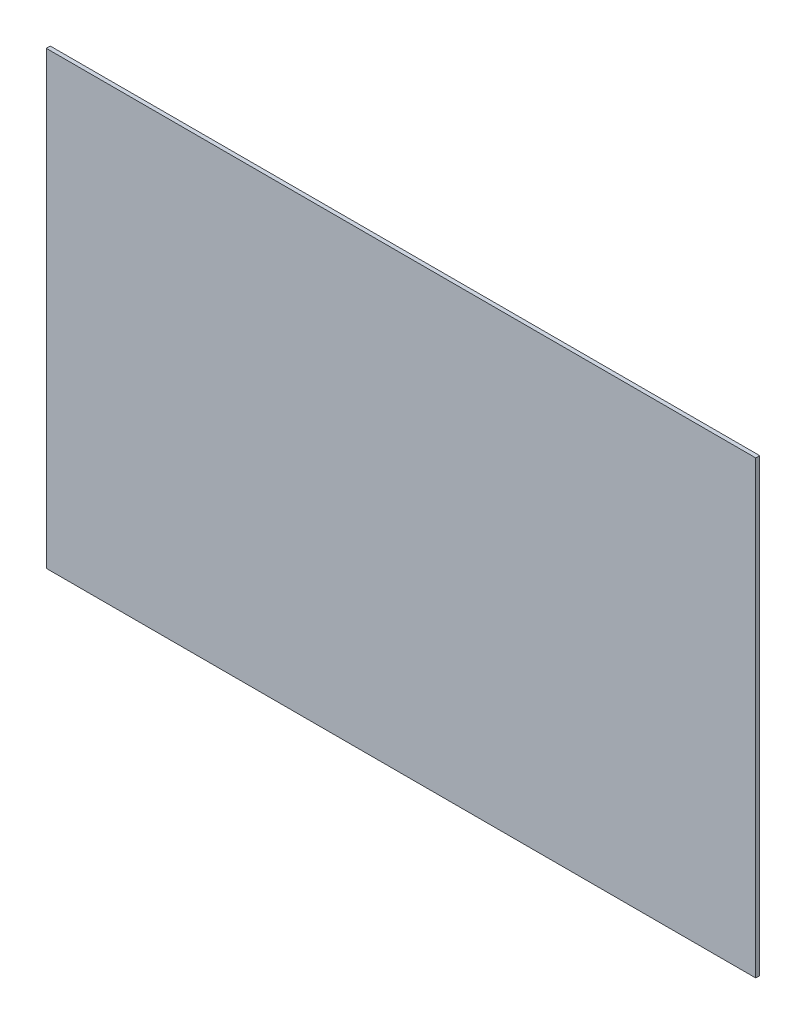
SolidWorks part; units mm, degrees
ref_plane "Plano frontal" through (0, 0, 0) normal (0, 0, 1) x (1, 0, 0)
ref_plane "Plano superior" through (0, 0, 0) normal (0, 1, 0) x (1, 0, 0)
ref_plane "Plano direito" through (0, 0, 0) normal (1, 0, 0) x (0, 0, -1)
sketch "Esboço1" plane through (0, 0, 0) normal (0, 0, 1) x (1, 0, 0)
  line L1 (-146.3409, 96.5423) -> (31.6591, 96.5423)
  line L2 (-146.3409, 96.5423) -> (-146.3409, -16.4577)
  line L3 (-146.3409, -16.4577) -> (31.6591, -16.4577)
  line L4 (31.6591, 96.5423) -> (31.6591, -16.4577)
  dimension "D1" = 113
  dimension "D2" = 178
extrude "Ressalto-extrusão1" add sketch "Esboço1" along normal blind 1
